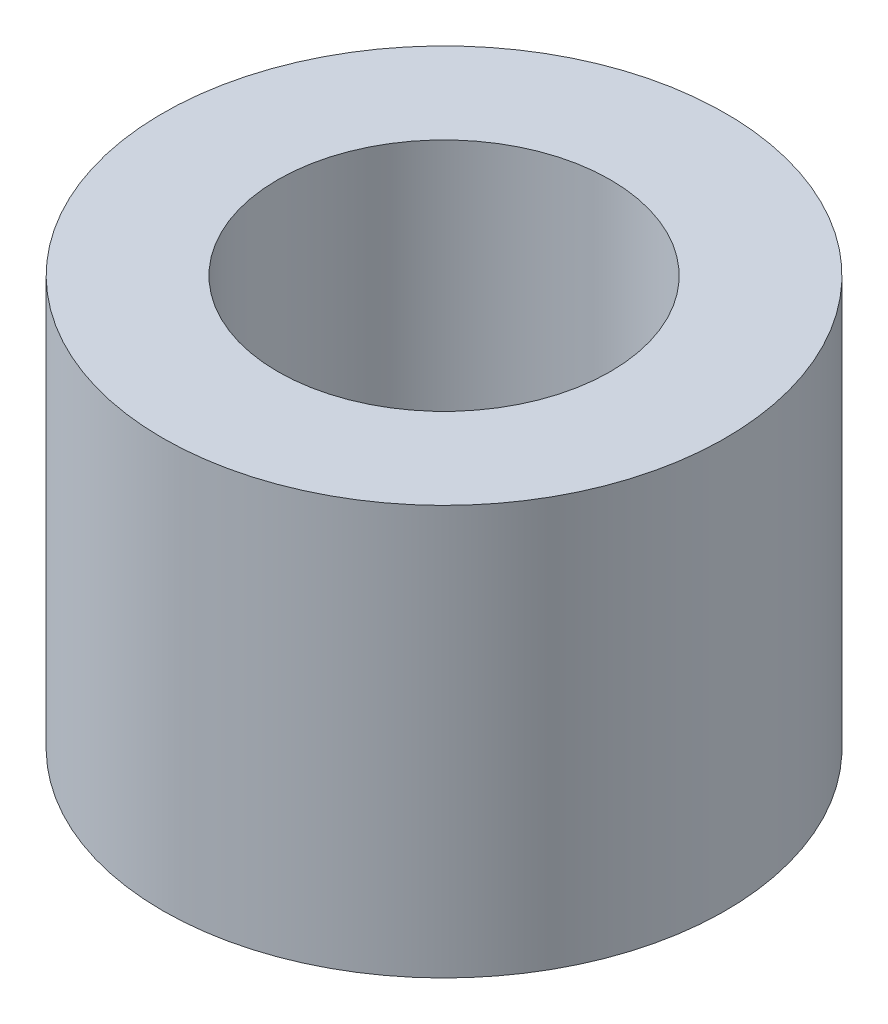
SolidWorks part; units mm, degrees
ref_plane "Front Plane" through (0, 0, 0) normal (0, 0, 1) x (1, 0, 0)
ref_plane "Top Plane" through (0, 0, 0) normal (0, 1, 0) x (1, 0, 0)
ref_plane "Right Plane" through (0, 0, 0) normal (1, 0, 0) x (0, 0, -1)
sketch "Sketch1" plane through (0, 0, 0) normal (0, 1, 0) x (1, 0, 0)
  circle A0 centre (0, 0) radius 2.75
  circle A1 centre (0, 0) radius 1.625
  dimension "D1" = 3.25
  dimension "D2" = 5.5
extrude "Boss-Extrude1" add sketch "Sketch1" along normal blind 4
